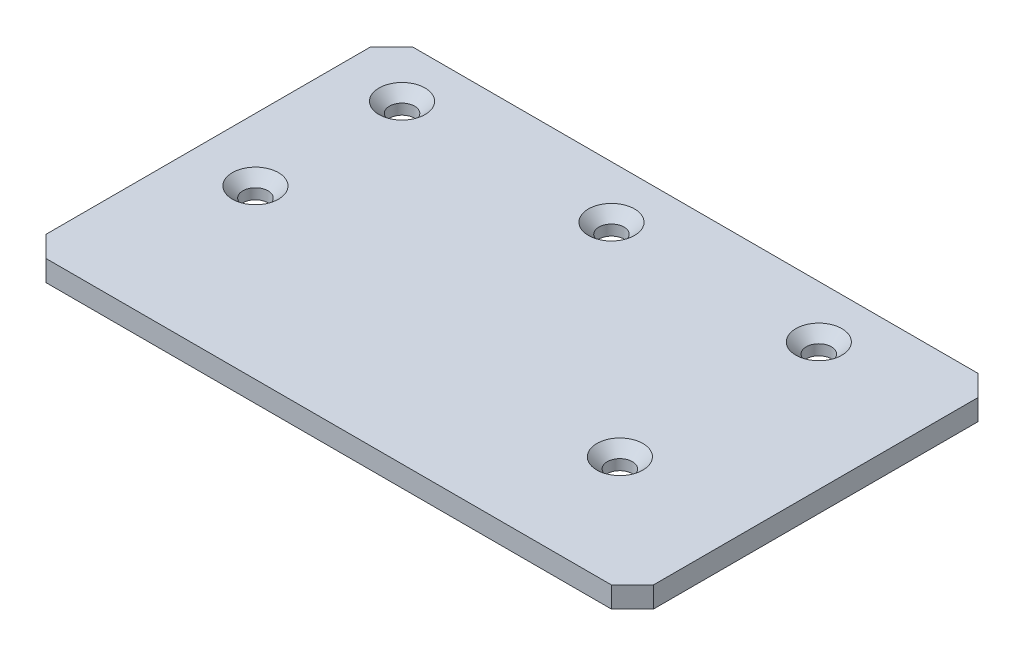
SolidWorks part; units mm, degrees
ref_plane "Front Plane" through (0, 0, 0) normal (0, 0, 1) x (1, 0, 0)
ref_plane "Top Plane" through (0, 0, 0) normal (0, 1, 0) x (1, 0, 0)
ref_plane "Right Plane" through (0, 0, 0) normal (1, 0, 0) x (0, 0, -1)
sketch "Sketch1" plane through (0, 0, 0) normal (0, 1, 0) x (1, 0, 0)
  line L1 (-29, -17.5) -> (29, -17.5)
  line L2 (-29, -17.5) -> (-29, 17.5)
  line L3 (-29, 17.5) -> (29, 17.5)
  line L4 (29, -17.5) -> (29, 17.5)
  line L5 (-29, -17.5) -> (29, 17.5) construction
  line L6 (-29, 17.5) -> (29, -17.5) construction
  point P0 (0, 0)
  dimension "D1" = 35
  dimension "D2" = 58
extrude "Boss-Extrude1" add sketch "Sketch1" along normal blind 2
hole_wizard "CSK for ST2.2 Cross recessed CTSK head tapping screws1" positions "Sketch2" profile "Sketch3" countersink size "ST2.2" standard "GB" end condition through all
sketch "Sketch2" plane through (0, 2, 0) normal (0, 1, 0) x (1, 0, 0)
  line L0 (-29, -17.5) -> (29, -17.5) construction
  line L1 (29, -17.5) -> (29, 17.5) construction
  point P0 (-23, 12.5)
  point P2 (-3, 12.5)
  point P4 (16.8, 12.5)
  point P6 (16.8, -6.5)
  point P8 (-23, -1.5)
  point P15 (0, 0)
  point P16 (0, 0)
  point P17 (0, 0)
  dimension "D1" = 11
  dimension "D2" = 19
  dimension "D3" = 12.2
  dimension "D4" = 19.8
  dimension "D5" = 20
  dimension "D6" = 16
sketch "Sketch3" plane through (-23, 2, -12.5) normal (1, 0, 0) x (0, 0, 1)
  line L0 (0, 0) -> (0, 2)
  line L1 (0, 2) -> (1.2, 2)
  line L2 (1.2, 2) -> (1.2, 1)
  line L3 (1.2, 1) -> (2.2, 0)
  line L5 (2.2, 0) -> (0, 0)
  line L6 (-1.2, 1) -> (-2.2, 0) construction
  line L11 (0, -6.35) -> (0, 107.95) construction
  dimension "Thru Hole Dia." = 2.4
  dimension "Thru Hole Depth" = 2
  dimension "Near C'Sink Dia." = 4.4
  dimension "Near C'Sink Angle" = 90
chamfer "Chamfer1" distance 2 angle 45 4 edges at (-29, 1, -17.5) (-29, 1, 17.5) (29, 1, 17.5) (29, 1, -17.5)
